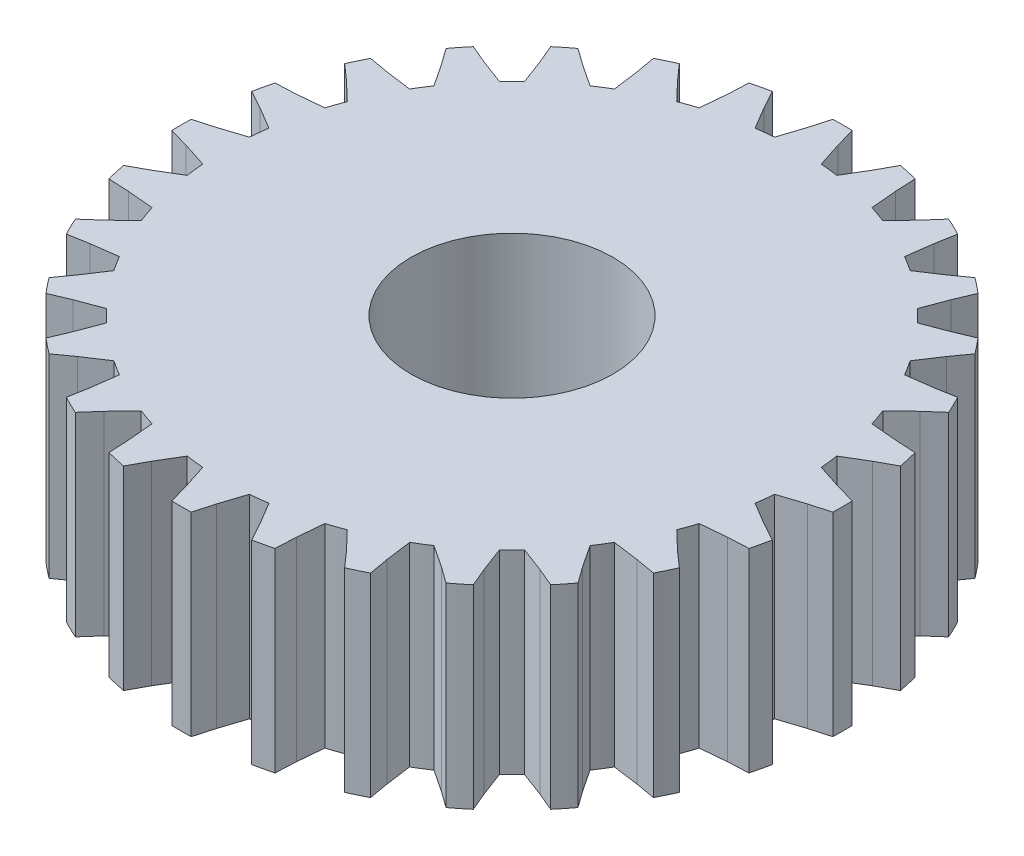
SolidWorks part; units mm, degrees
ref_plane "Front Plane" through (0, 0, 0) normal (0, 0, 1) x (1, 0, 0)
ref_plane "Top Plane" through (0, 0, 0) normal (0, 1, 0) x (1, 0, 0)
ref_plane "Right Plane" through (0, 0, 0) normal (1, 0, 0) x (0, 0, -1)
sketch "Sketch2" plane through (0, 0, 0) normal (0, 1, 0) x (1, 0, 0)
  line L0 (0, -12.2959) -> (0, 12.2959) construction
  line L1 (0.3925, 7.9904) -> (0.6, 7.3506)
  line L2 (0.3925, 7.9904) -> (0.25, 8.4963)
  line L3 (-0.3925, 7.9904) -> (-0.6, 7.3506)
  line L4 (-0.3925, 7.9904) -> (-0.25, 8.4963)
  arc A0 (0.25, 8.4963) -> (-0.25, 8.4963) centre (0, 0) ccw
  circle A1 centre (0, 0) radius 8 construction
  circle A2 centre (0, 0) radius 7.375
  circle A3 centre (0, 0) radius 2.6
  point P5 (0.2303, 8.5)
  point P8 (0, 0)
  point P9 (0, 8.5)
  point P10 (0, 7.375)
  point P12 (0.95, 7.3136)
  point P15 (0.3925, 7.9904)
  point P16 (-0.3925, 7.9904)
  dimension "D1" = 17
  dimension "D2" = 14.75
  dimension "D3" = 16
  dimension "D10" = 5.2
  dimension "D4" = 0.3925
  dimension "D5" = 0.25
  dimension "D6" = 0.6
  dimension "D7" = 0.3925
extrude "Boss-Extrude1" add sketch "Sketch2" along normal blind 5
pattern_circular "CirPattern1" count 28 over 360 about axis through (0, 0, 0) along (0, 1, 0) of "Boss-Extrude1"
sketch "Sketch3" plane through (0, 0, 0) normal (1, 0, 0) x (0, 0, -1)
  line L0 (0, -18.674) -> (0, 18.674) construction
  point P4 (0, 0)
